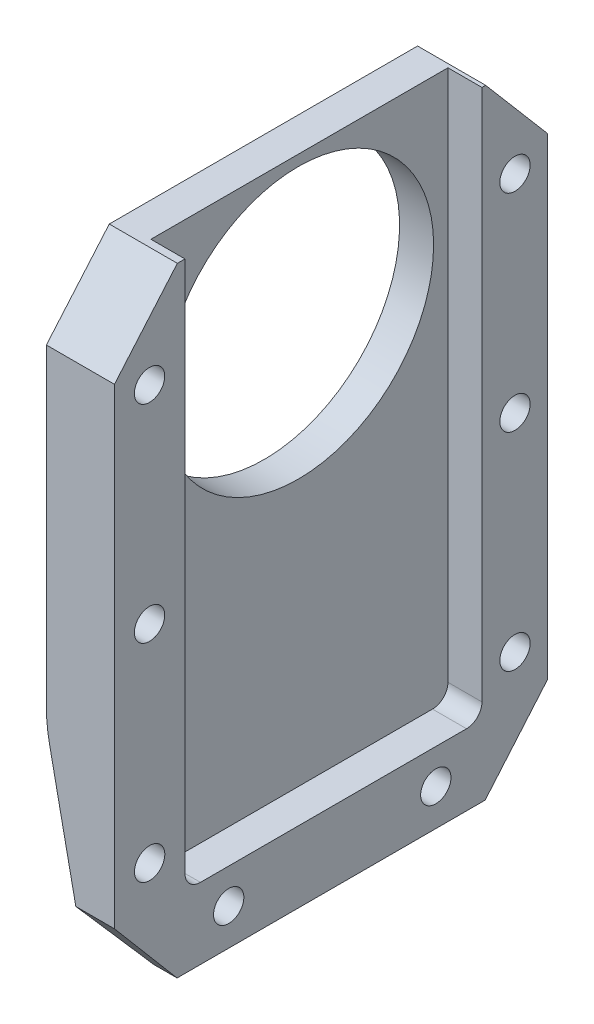
SolidWorks part; units mm, degrees
material "PET"
ref_plane "Front Plane" through (0, 0, 0) normal (0, 0, 1) x (1, 0, 0)
ref_plane "Top Plane" through (0, 0, 0) normal (0, 1, 0) x (1, 0, 0)
ref_plane "Right Plane" through (0, 0, 0) normal (1, 0, 0) x (0, 0, -1)
sketch "Sketch1" plane through (0, 0, 0) normal (0, 0, 1) x (1, 0, 0)
  line L0 (0, 0) -> (0, 50.8)
  line L1 (0, 50.8) -> (-5.588, 50.8)
  line L2 (-5.588, 50.8) -> (-5.588, 17.78)
  line L3 (-5.588, 17.78) -> (-1.9166, 0)
  line L4 (-1.9166, 0) -> (0, 0)
extrude "Boss-Extrude1" add sketch "Sketch1" along normal blind 35.56
fillet "Fillet1" radius 12.7 1 edges at (-5.588, 17.78, 17.78)
sketch "Sketch6" plane through (0, 0, 0) normal (1, 0, 0) x (0, 0, -1)
  line L0 (-17.78, 50.8) -> (-17.78, 0) construction
  line L1 (-35.56, 50.8) -> (0, 50.8) construction
  line L2 (-35.56, 0) -> (0, 0) construction
  line L4 (-29.772, 50.8) -> (-5.388, 50.8)
  line L5 (-29.772, 50.8) -> (-29.772, 5.842)
  line L6 (-29.772, 5.842) -> (-5.388, 5.842)
  line L7 (-5.388, 50.8) -> (-5.388, 5.842)
  dimension "D1" = 44.958
  dimension "D2" = 24.384
extrude "Cut-Extrude1" cut sketch "Sketch6" against normal blind 2.794
fillet "Fillet2" radius 1.27 2 edges at (-1.397, 5.842, 29.772) (-1.397, 5.842, 5.388)
sketch "Sketch10" plane through (0, 0, 0) normal (1, 0, 0) x (0, 0, -1)
  line L0 (-35.56, 44.7804) -> (-30.3976, 50.8)
  line L1 (-35.56, 0) -> (-35.56, 50.8) construction
  line L2 (-35.56, 50.8) -> (-29.772, 50.8) construction
  line L3 (-30.3976, 50.8) -> (-35.56, 50.8)
  line L4 (-35.56, 50.8) -> (-35.56, 44.7804)
extrude "Cut-Extrude3" cut sketch "Sketch10" against normal through all
sketch "Sketch11" plane through (0, 0, 0) normal (1, 0, 0) x (0, 0, -1)
  line L0 (-5.0855, 50.8) -> (0, 50.8)
  line L1 (-5.388, 50.8) -> (0, 50.8) construction
  line L2 (0, 50.8) -> (0, 44.8249)
  line L3 (0, 0) -> (0, 50.8) construction
  line L4 (0, 44.8249) -> (-5.0855, 50.8)
  line L5 (0, 6.0295) -> (-5.1287, 0)
  line L6 (-35.56, 0) -> (0, 0) construction
  line L7 (-5.1287, 0) -> (0, 0)
  line L8 (0, 0) -> (0, 6.0295)
  line L9 (-35.56, 6.0712) -> (-35.56, 0)
  line L10 (-35.56, 0) -> (-35.56, 44.7804) construction
  line L11 (-35.56, 0) -> (-30.4171, 0)
  line L12 (-30.4171, 0) -> (-35.56, 6.0712)
extrude "Cut-Extrude4" cut sketch "Sketch11" against normal through all
hole_wizard "7/8 (0.875) Diameter Hole1" positions "Sketch12" profile "Sketch13" hole size "7/8" standard "ANSI Inch" end condition through all
sketch "Sketch12" plane through (-5.588, 0, 0) normal (-1, 0, 0) x (0, 0, 1)
  point P0 (17.6785, 38.8095)
sketch "Sketch13" plane through (-5.588, 38.8095, 17.6785) normal (0, 1, 0) x (0, 0, 1)
  line L0 (0, 0) -> (0, 5.588)
  line L1 (0, 5.588) -> (11.1125, 5.588)
  line L2 (11.1125, 5.588) -> (11.1125, 0)
  line L5 (11.1125, 0) -> (0, 0)
  line L11 (0, -6.35) -> (0, 107.95) construction
  dimension "Thru Hole Dia." = 22.225
  dimension "Thru Hole Depth" = 5.588
hole_wizard "#40 (0.098) Diameter Hole1" positions "Sketch14" profile "Sketch15" hole size "#40" standard "ANSI Inch" end condition through all
sketch "Sketch14" plane through (-5.588, 0, 0) normal (-1, 0, 0) x (0, 0, 1)
  point P0 (2.6785, 43.3095)
  point P3 (2.6785, 26.3095)
  point P6 (2.6785, 9.3095)
  point P9 (9.1785, 3.0095)
  point P12 (26.1819, 2.9992)
  point P14 (32.6729, 9.2992)
  point P16 (32.6785, 26.3095)
  point P19 (32.6785, 43.2992)
sketch "Sketch15" plane through (-5.588, 43.3095, 2.6785) normal (0, 1, 0) x (0, 0, 1)
  line L0 (0, 0) -> (0, 5.588)
  line L1 (0, 5.588) -> (1.2446, 5.588)
  line L2 (1.2446, 5.588) -> (1.2446, 0.635)
  line L3 (1.2446, 0.635) -> (1.8796, 0)
  line L5 (1.8796, 0) -> (0, 0)
  line L6 (-1.2446, 0.635) -> (-1.8796, 0) construction
  line L11 (0, -6.35) -> (0, 107.95) construction
  dimension "Thru Hole Dia." = 2.4892
  dimension "Thru Hole Depth" = 5.588
  dimension "Near C'Sink Dia." = 3.7592
  dimension "Near C'Sink Angle" = 90
